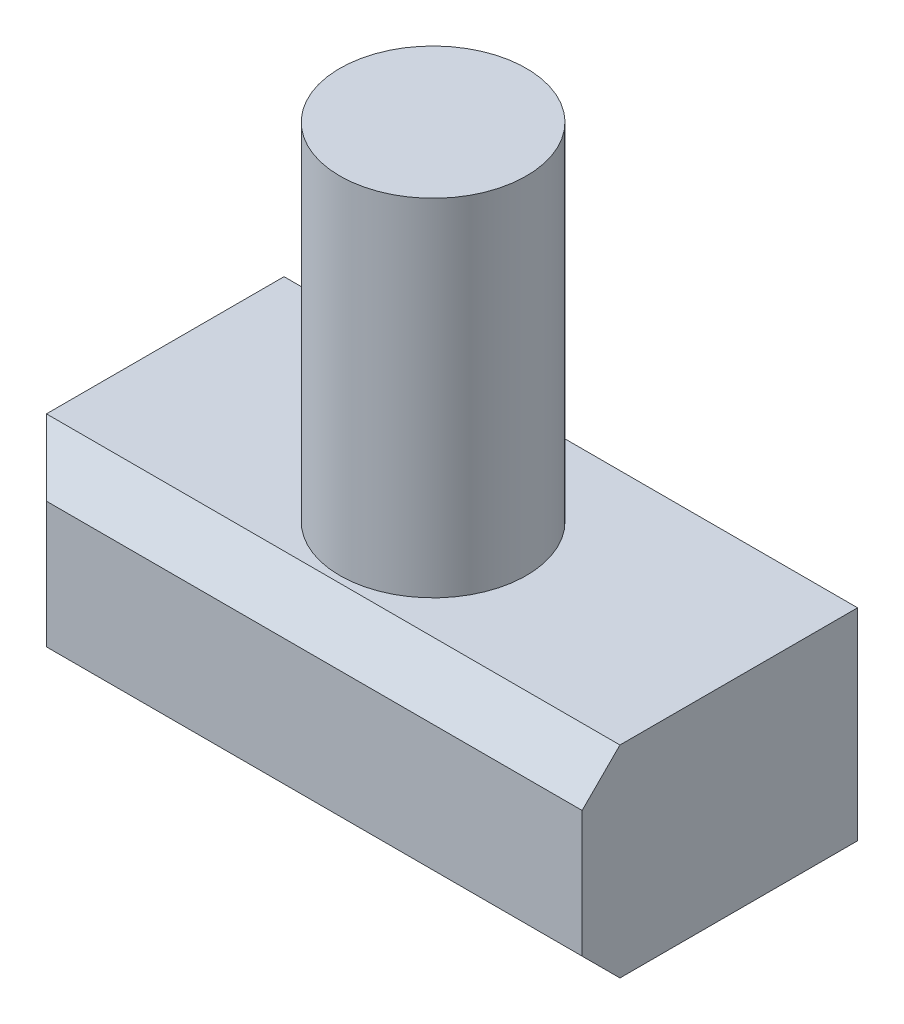
SolidWorks part; units mm, degrees
ref_plane "Front Plane" through (0, 0, 0) normal (0, 0, 1) x (1, 0, 0)
ref_plane "Top Plane" through (0, 0, 0) normal (0, 1, 0) x (1, 0, 0)
ref_plane "Right Plane" through (0, 0, 0) normal (1, 0, 0) x (0, 0, -1)
sketch "Sketch1" plane through (0, 0, 0) normal (0, 1, 0) x (1, 0, 0)
  line L1 (-122.7146, 58.9329) -> (122.7146, 58.9329)
  line L2 (-122.7146, 58.9329) -> (-122.7146, -58.9329)
  line L3 (-122.7146, -58.9329) -> (122.7146, -58.9329)
  line L4 (122.7146, 58.9329) -> (122.7146, -58.9329)
  point P0 (0, 0)
extrude "Boss-Extrude1" add sketch "Sketch1" along normal blind 86.36
chamfer "Chamfer1" distance 16.18 angle 45 4 edges at (0, 86.36, 58.9329) (122.7146, 86.36, 0) (-122.7146, 43.18, 58.9329) (0, 0, 58.9329)
sketch "Sketch2" plane through (0, 86.36, 0) normal (0, 1, 0) x (1, 0, 0)
  circle A0 centre (0, 0) radius 39.9158
  point P3 (0, 0)
extrude "Boss-Extrude2" add sketch "Sketch2" along normal blind 148.082
